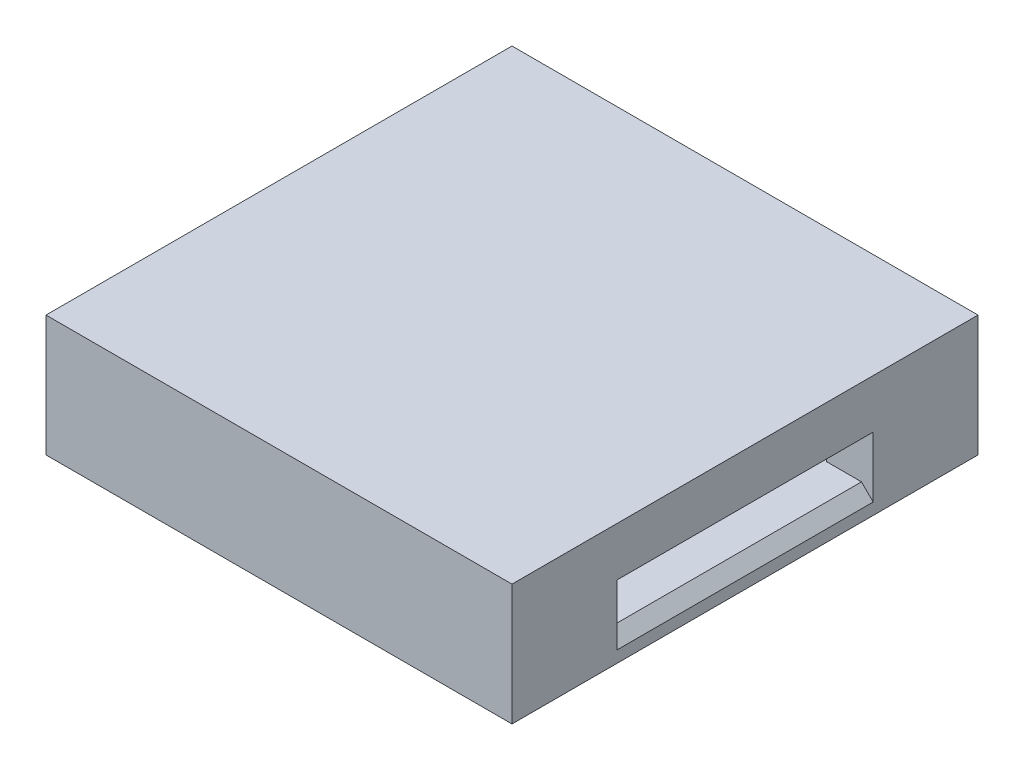
SolidWorks part; units mm, degrees
ref_plane "Front Plane" through (0, 0, 0) normal (0, 0, 1) x (1, 0, 0)
ref_plane "Top Plane" through (0, 0, 0) normal (0, 1, 0) x (1, 0, 0)
ref_plane "Right Plane" through (0, 0, 0) normal (1, 0, 0) x (0, 0, -1)
sketch "Sketch1" plane through (0, 0, 0) normal (0, 1, 0) x (1, 0, 0)
  line L1 (0, 0) -> (20, 0)
  line L2 (0, 0) -> (0, 20)
  line L3 (0, 20) -> (20, 20)
  line L4 (20, 0) -> (20, 20)
  dimension "D1" = 20
  dimension "D2" = 20
extrude "Boss-Extrude1" add sketch "Sketch1" along normal blind 1
sketch "Sketch2" plane through (0, 1, 0) normal (0, 1, 0) x (1, 0, 0)
  line L0 (20, 0) -> (20, 20) construction
  line L1 (20, 15.5) -> (4, 15.5)
  line L2 (20, 15.5) -> (20, 4.5)
  line L3 (20, 4.5) -> (4, 4.5)
  line L4 (4, 15.5) -> (4, 4.5)
  line L6 (0, 0) -> (20, 0) construction
  line L8 (2, 18.05) -> (18, 18.05)
  line L9 (2, 18.05) -> (2, 1.95)
  line L10 (2, 1.95) -> (18, 1.95)
  line L11 (18, 18.05) -> (18, 1.95)
  point P12 (18, 10)
  point P13 (20, 10)
  line M9 (0, 20) -> (0, 0)
  line M10 (0, 0) -> (20, 0)
  line M11 (20, 0) -> (20, 20)
  line M12 (20, 20) -> (0, 20)
  dimension "D1" = 11
  dimension "D2" = 4.5
  dimension "D3" = 16
  dimension "D4" = 16.1
  dimension "D5" = 0
  dimension "D6" = 16
  dimension "D7" = 2
extrude "Boss-Extrude2" add sketch "Sketch2" along normal blind 2.1 contours L8 L11 L1 L3 L10 L9 M11 M12 M9 M10
chamfer "Chamfer1" distance 0.5 angle 45 1 edges at (20, 1, -10)
sketch "Sketch3" plane through (0, 3.1, 0) normal (0, 1, 0) x (1, 0, 0)
  line L1 (0, 20) -> (20, 20)
  line L2 (0, 20) -> (0, 0)
  line L3 (0, 0) -> (20, 0)
  line L4 (20, 20) -> (20, 0)
extrude "Boss-Extrude3" add sketch "Sketch3" along normal blind 2.1
